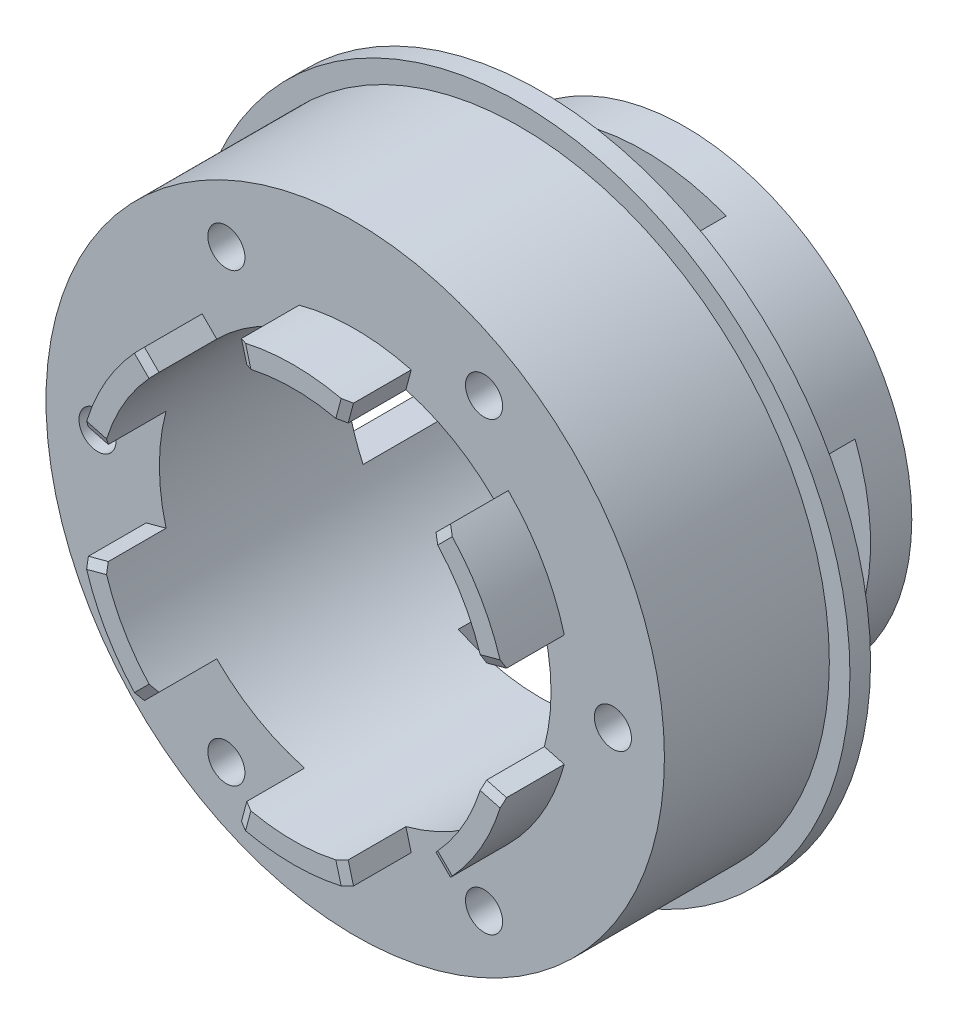
SolidWorks part; units mm, degrees
ref_plane "정면" through (0, 0, 0) normal (0, 0, 1) x (1, 0, 0)
ref_plane "윗면" through (0, 0, 0) normal (0, 1, 0) x (1, 0, 0)
ref_plane "우측면" through (0, 0, 0) normal (1, 0, 0) x (0, 0, -1)
sketch "스케치1" plane through (0, 0, 0) normal (0, 0, 1) x (1, 0, 0)
  circle A0 centre (0, 0) radius 11
  dimension "D1" = 22
extrude "보스-돌출1" add sketch "스케치1" along normal blind 2
sketch "스케치2" plane through (0, 0, 2) normal (0, 0, 1) x (1, 0, 0)
  circle A0 centre (0, 0) radius 11
  circle A1 centre (0, 0) radius 9.5
  circle A5 centre (0, 0) radius 11 construction
  dimension "D1" = 1.5
extrude "보스-돌출2" add sketch "스케치2" along normal blind 5
sketch "스케치4" plane through (0, 0, 7) normal (0, 0, 1) x (1, 0, 0)
  circle A0 centre (0, 0) radius 16
  circle A1 centre (0, 0) radius 9.5
  circle A2 centre (0, 0) radius 9.5 construction
  dimension "D1" = 32
extrude "보스-돌출3" add sketch "스케치4" along normal blind 1
sketch "스케치5" plane through (0, 0, 8) normal (0, 0, 1) x (1, 0, 0)
  circle A0 centre (0, 0) radius 9.5
  circle A1 centre (0, 0) radius 15
  circle A2 centre (0, 0) radius 9.5 construction
  dimension "D1" = 30
extrude "보스-돌출4" add sketch "스케치5" along normal blind 8
sketch "스케치6" plane through (0, 0, 16) normal (0, 0, 1) x (1, 0, 0)
  circle A0 centre (0, 0) radius 12.5 construction
  circle A6 centre (0, 0) radius 9.5 construction
  circle A8 centre (12.5, 0) radius 0.9
  circle A9 centre (6.25, -10.8253) radius 0.9
  circle A10 centre (-6.25, -10.8253) radius 0.9
  circle A11 centre (-12.5, 0) radius 0.9
  circle A12 centre (-6.25, 10.8253) radius 0.9
  circle A13 centre (6.25, 10.8253) radius 0.9
  point P19 (0, 0)
  point P20 (0, 0)
  dimension "D1" = 3
  dimension "D2" = 1.8
  dimension "D3" = 6
extrude "컷-돌출1" cut sketch "스케치6" against normal blind 8
sketch "스케치7" plane through (0, 0, 0) normal (0, 0, -1) x (-1, 0, 0)
  circle A0 centre (0, 0) radius 8 construction
  circle A5 centre (0, 0) radius 3
  circle A6 centre (-8, 0) radius 1
  circle A7 centre (8, 0) radius 1
  circle A9 centre (0, 8) radius 1
  circle A11 centre (0, -8) radius 1
  dimension "D1" = 16
  dimension "D2" = 2
  dimension "D4" = 6
extrude "컷-돌출2" cut sketch "스케치7" against normal through all
sketch "스케치8" plane through (0, 0, 0) normal (0, 1, 0) x (1, 0, 0)
  line L0 (11, 0) -> (-11, 0) construction
  line L1 (-4, -2) -> (4, -2)
  line L2 (-4, -2) -> (-4, -7)
  line L3 (-4, -7) -> (4, -7)
  line L4 (4, -2) -> (4, -7)
  line L5 (-4, -2) -> (4, -7) construction
  line L6 (-4, -7) -> (4, -2) construction
  line L8 (11, -7) -> (11, 0) construction
  line L9 (-11, 0) -> (-11, -7) construction
  line L10 (11, -7) -> (-11, -7) construction
  point P0 (0, -4.5)
  dimension "D1" = 2
  dimension "D3" = 7
  dimension "D4" = 7
extrude "컷-돌출3" cut sketch "스케치8" against normal through all both and the other way through all
sketch "스케치9" plane through (0, 0, 0) normal (1, 0, 0) x (0, 0, -1)
  line L0 (-7, -10.247) -> (-7, 10.247) construction
  line L1 (-7, -4) -> (-2, -4)
  line L2 (-7, -4) -> (-7, 4)
  line L3 (-7, 4) -> (-2, 4)
  line L4 (-2, -4) -> (-2, 4)
  line L5 (0, 11) -> (-2, 11) construction
  line L6 (-2, -11) -> (0, -11) construction
  line L7 (0, -11) -> (0, 11) construction
  dimension "D1" = 7
  dimension "D2" = 7
  dimension "D3" = 2
extrude "컷-돌출4" cut sketch "스케치9" against normal through all both and the other way through all
sketch "스케치10" plane through (0, 0, 16) normal (0, 0, 1) x (1, 0, 0)
  line L1 (2.4588, 9.1763) -> (2.7176, 10.1422)
  line L3 (6.7175, 6.7175) -> (7.4246, 7.4246)
  line L5 (9.1763, 2.4588) -> (10.1422, 2.7176)
  line L7 (9.1763, -2.4588) -> (10.1422, -2.7176)
  line L9 (6.7175, -6.7175) -> (7.4246, -7.4246)
  line L11 (2.4588, -9.1763) -> (2.7176, -10.1422)
  line L13 (-2.4588, -9.1763) -> (-2.7176, -10.1422)
  line L15 (-6.7175, -6.7175) -> (-7.4246, -7.4246)
  line L17 (-9.1763, -2.4588) -> (-10.1422, -2.7176)
  line L19 (-9.1763, 2.4588) -> (-10.1422, 2.7176)
  line L21 (-6.7175, 6.7175) -> (-7.4246, 7.4246)
  line L23 (-2.4588, 9.1763) -> (-2.7176, 10.1422)
  arc A0 (-7.4246, 7.4246) -> (-10.1422, 2.7176) centre (0, 0) ccw
  arc A1 (-9.1763, -2.4588) -> (-6.7175, -6.7175) centre (0, 0) ccw
  arc A2 (2.7176, 10.1422) -> (-2.7176, 10.1422) centre (0, 0) ccw
  arc A3 (10.1422, 2.7176) -> (7.4246, 7.4246) centre (0, 0) ccw
  arc A4 (7.4246, -7.4246) -> (10.1422, -2.7176) centre (0, 0) ccw
  arc A5 (-2.7176, -10.1422) -> (2.7176, -10.1422) centre (0, 0) ccw
  arc A6 (-10.1422, -2.7176) -> (-7.4246, -7.4246) centre (0, 0) ccw
  arc A7 (-2.4588, -9.1763) -> (2.4588, -9.1763) centre (0, 0) ccw
  arc A8 (6.7175, -6.7175) -> (9.1763, -2.4588) centre (0, 0) ccw
  arc A9 (9.1763, 2.4588) -> (6.7175, 6.7175) centre (0, 0) ccw
  arc A10 (2.4588, 9.1763) -> (-2.4588, 9.1763) centre (0, 0) ccw
  arc A11 (-6.7175, 6.7175) -> (-9.1763, 2.4588) centre (0, 0) ccw
  point P30 (0, 0)
  dimension "D1" = 1
extrude "보스-돌출5" add sketch "스케치10" along normal blind 3
chamfer "모따기1" distance 0.2 angle 64 12 edges at (-9.6593, -2.5882, 19) (-7.0711, -7.0711, 19) (-2.5882, -9.6593, 19) (2.5882, -9.6593, 19) (7.0711, -7.0711, 19) (9.6593, -2.5882, 19) (9.6593, 2.5882, 19) (7.0711, 7.0711, 19) (2.5882, 9.6593, 19) (-2.5882, 9.6593, 19) (-7.0711, 7.0711, 19) (-9.6593, 2.5882, 19)
